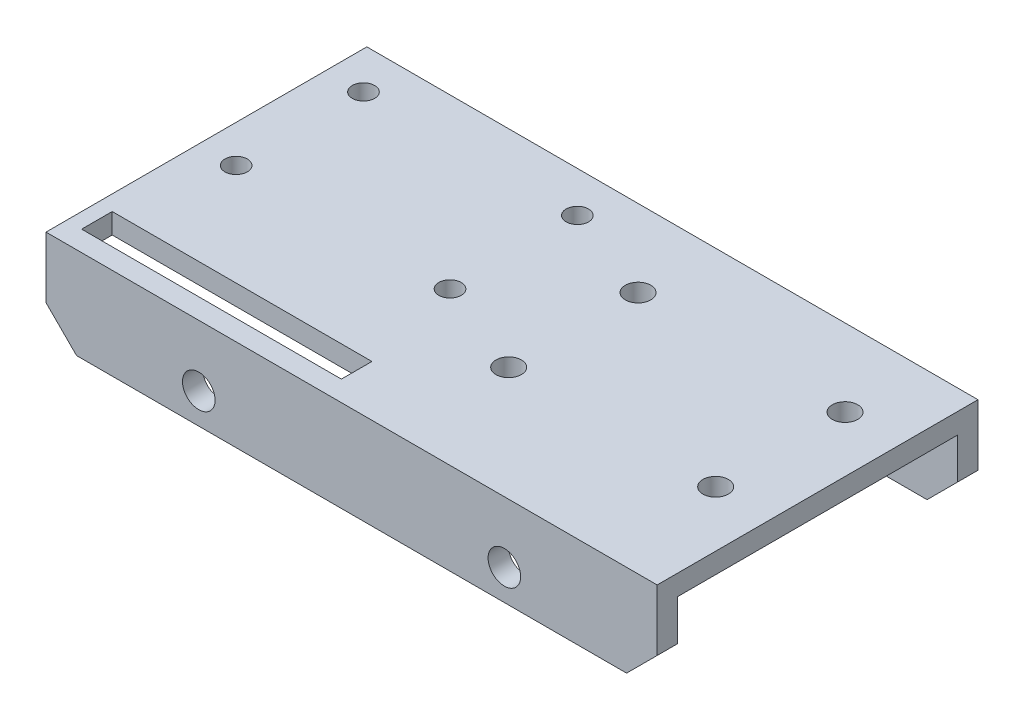
SolidWorks part; units mm, degrees
ref_plane "Front Plane" through (0, 0, 0) normal (0, 0, 1) x (1, 0, 0)
ref_plane "Top Plane" through (0, 0, 0) normal (0, 1, 0) x (1, 0, 0)
ref_plane "Right Plane" through (0, 0, 0) normal (1, 0, 0) x (0, 0, -1)
sketch "Sketch1" plane through (0, 0, 0) normal (0, 1, 0) x (1, 0, 0)
  line L1 (-30, 15.75) -> (30, 15.75)
  line L2 (-30, 15.75) -> (-30, -15.75)
  line L3 (-30, -15.75) -> (30, -15.75)
  line L4 (30, 15.75) -> (30, -15.75)
  line L5 (-30, 15.75) -> (30, -15.75) construction
  line L6 (-30, -15.75) -> (30, 15.75) construction
  point P0 (0, 0)
  dimension "D1" = 31.5
  dimension "D2" = 60
extrude "Boss-Extrude1" add sketch "Sketch1" along normal blind 2
sketch "Sketch2" plane through (0, 0, 0) normal (0, -1, 0) x (1, 0, 0)
  line L0 (-30, -15.75) -> (-30, 15.75) construction
  line L1 (30, -15.75) -> (-30, -15.75)
  line L2 (30, -15.75) -> (30, -13.75)
  line L3 (30, -13.75) -> (-30, -13.75)
  line L4 (-30, -15.75) -> (-30, -13.75)
  line L6 (30, 15.75) -> (-30, 15.75)
  line L7 (30, 15.75) -> (30, 13.75)
  line L8 (30, 13.75) -> (-30, 13.75)
  line L9 (-30, 15.75) -> (-30, 13.75)
  dimension "D1" = 2
  dimension "D2" = 2
extrude "Boss-Extrude2" add sketch "Sketch2" along normal blind 7
sketch "Sketch3" plane through (0, 0, -15.75) normal (0, 0, -1) x (-1, 0, 0)
  line L0 (0, -7) -> (0, 2) construction
  line L1 (30, -7) -> (-30, -7) construction
  line L2 (-30, 2) -> (30, 2) construction
  line L3 (30, -7) -> (0, -7) construction
  line L4 (15, -7) -> (15, 2) construction
  circle A0 centre (15, -4) radius 1.6
  circle A1 centre (-15, -4) radius 1.6
  dimension "D1" = 3.2
  dimension "D2" = 3
extrude "Cut-Extrude1" cut sketch "Sketch3" against normal through all both and the other way through all
chamfer "Chamfer1" distance 3 angle 45 2 edges at (-30, -7, -14.75) (30, -7, -14.75)
chamfer "Chamfer3" distance 3 angle 45 2 edges at (30, -7, 14.75) (-30, -7, 14.75)
sketch "Sketch5" plane through (0, 0, 0) normal (0, -1, 0) x (1, 0, 0)
  line L0 (-30, -13.75) -> (-30, 13.75) construction
  line L1 (-28.5, 13.75) -> (-3, 13.75)
  line L2 (-28.5, 13.75) -> (-28.5, 10.75)
  line L3 (-28.5, 10.75) -> (-3, 10.75)
  line L4 (-3, 13.75) -> (-3, 10.75)
  line L5 (-30, 13.75) -> (30, 13.75) construction
  dimension "D1" = 1.5
  dimension "D2" = 25.5
  dimension "D3" = 3
  dimension "D4" = 0
extrude "Cut-Extrude3" cut sketch "Sketch5" against normal blind 10
sketch "Sketch6" plane through (0, 2, 0) normal (0, 1, 0) x (1, 0, 0)
  circle A0 centre (24.525, 8.169) radius 1.25 construction
  circle A1 centre (24.525, -4.531) radius 1.25 construction
  circle A2 centre (4.205, -4.531) radius 1.25 construction
  circle A3 centre (4.205, 8.169) radius 1.25 construction
  circle A4 centre (-5.335, 11.75) radius 1.1 construction
  circle A5 centre (-5.335, -0.75) radius 1.1 construction
  circle A6 centre (-26.335, -0.75) radius 1.1 construction
  circle A7 centre (-26.335, 11.75) radius 1.1 construction
  circle A8 centre (24.525, 8.169) radius 1.25
  circle A9 centre (24.525, -4.531) radius 1.25
  circle A10 centre (4.205, -4.531) radius 1.25
  circle A11 centre (4.205, 8.169) radius 1.25
  circle A12 centre (-5.335, 11.75) radius 1.1
  circle A13 centre (-5.335, -0.75) radius 1.1
  circle A14 centre (-26.335, -0.75) radius 1.1
  circle A15 centre (-26.335, 11.75) radius 1.1
extrude "Cut-Extrude4" cut sketch "Sketch6" against normal blind 10
equation "\"D2@Sketch2\"=\"D1@Sketch2\""
